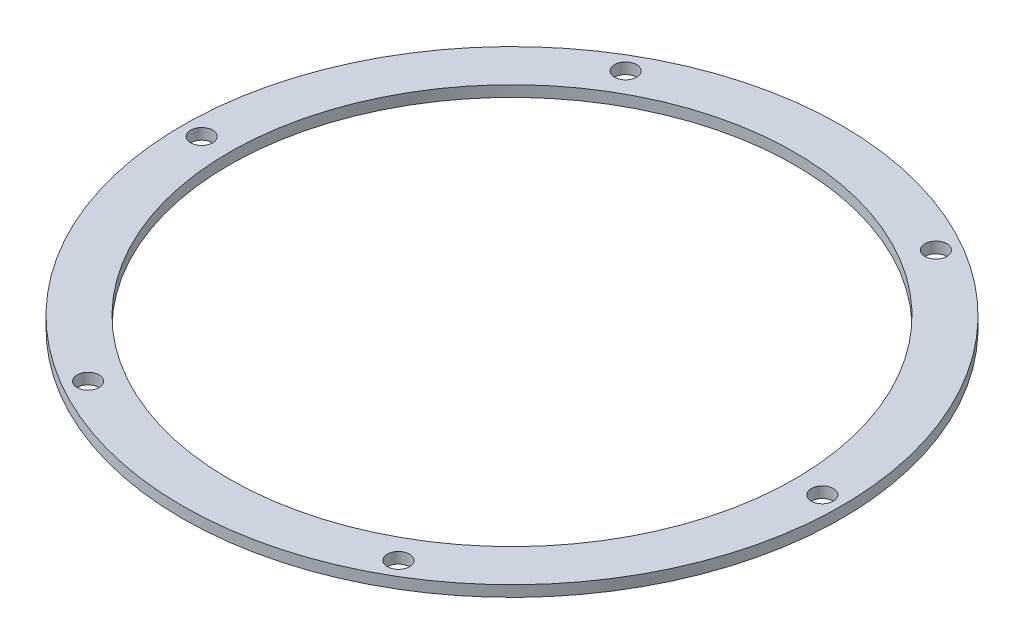
SolidWorks part; units mm, degrees
material "Thornel Mat VMA"
ref_plane "前视基准面" through (0, 0, 0) normal (0, 0, 1) x (1, 0, 0)
ref_plane "上视基准面" through (0, 0, 0) normal (0, 1, 0) x (1, 0, 0)
ref_plane "右视基准面" through (0, 0, 0) normal (1, 0, 0) x (0, 0, -1)
sketch "草图1" plane through (0, 0, 0) normal (0, 1, 0) x (1, 0, 0)
  circle A0 centre (0, 0) radius 56.5 construction
  circle A1 centre (0, 0) radius 60
  circle A2 centre (-28.25, 48.9304) radius 2
  circle A3 centre (28.25, 48.9304) radius 2
  circle A4 centre (56.5, 0) radius 2
  circle A5 centre (28.25, -48.9304) radius 2
  circle A6 centre (0, 0) radius 51.5
  circle A7 centre (-28.25, -48.9304) radius 2
  circle A8 centre (-56.5, 0) radius 2
  point P16 (0, 0)
  dimension "D1" = 3.5
  dimension "D2" = 4
  dimension "D3" = 5
  dimension "D4" = 120
  dimension "D5" = 6
extrude "凸台-拉伸1" add sketch "草图1" along normal blind 2
